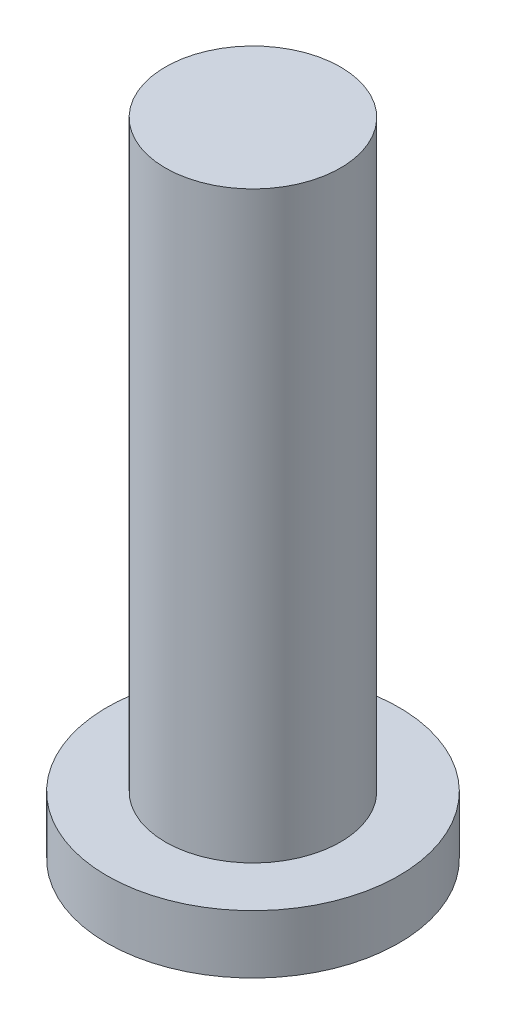
SolidWorks part; units mm, degrees
ref_plane "Front Plane" through (0, 0, 0) normal (0, 0, 1) x (1, 0, 0)
ref_plane "Top Plane" through (0, 0, 0) normal (0, 1, 0) x (1, 0, 0)
ref_plane "Right Plane" through (0, 0, 0) normal (1, 0, 0) x (0, 0, -1)
sketch "Sketch2" plane through (0, 0, 0) normal (0, 1, 0) x (1, 0, 0)
  circle A0 centre (0, 0) radius 12.5
  dimension "D1" = 25
extrude "Boss-Extrude1" add sketch "Sketch2" along normal blind 5
sketch "Sketch3" plane through (0, 5, 0) normal (0, 1, 0) x (1, 0, 0)
  circle A0 centre (0, 0) radius 7.5
  dimension "D1" = 15
extrude "Boss-Extrude2" add sketch "Sketch3" along normal blind 50
